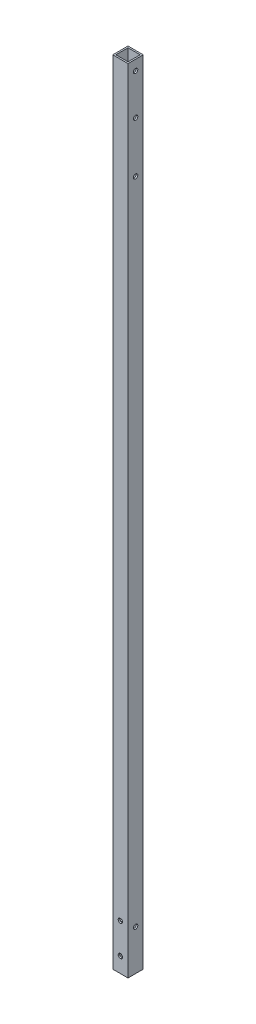
SolidWorks part; units mm, degrees
material "5052-H34"
ref_plane "正面" through (0, 0, 0) normal (0, 0, 1) x (1, 0, 0)
ref_plane "平面" through (0, 0, 0) normal (0, 1, 0) x (1, 0, 0)
ref_plane "右側面" through (0, 0, 0) normal (1, 0, 0) x (0, 0, -1)
sketch "ｽｹｯﾁ1" plane through (0, 0, 0) normal (0, 1, 0) x (1, 0, 0)
  line L1 (0, 0) -> (15, 0)
  line L2 (0, 0) -> (0, 15)
  line L3 (0, 15) -> (15, 15)
  line L4 (15, 0) -> (15, 15)
  dimension "D1" = 15
  dimension "D2" = 15
extrude "押し出し-薄板1" add sketch "ｽｹｯﾁ1" along normal blind 780 thin thin type one direction reverse wall 1.5
sketch "ｽｹｯﾁ2" plane through (15, 0, 0) normal (1, 0, 0) x (0, 0, -1)
  line L0 (7.5, 780) -> (7.5, 0) construction
  line L1 (0, 780) -> (15, 780) construction
  line L2 (0, 0) -> (15, 0) construction
  line L3 (15, 390) -> (0, 390) construction
  line L4 (15, 780) -> (15, 0) construction
  line L5 (0, 780) -> (0, 0) construction
  circle A4 centre (7.5, 730) radius 2.15
  circle A5 centre (7.5, 680) radius 2.15
  circle A6 centre (7.5, 40) radius 2.15
  circle A8 centre (7.5, 120) radius 2.15 construction
  circle A9 centre (7.5, 10) radius 2.15 construction
  circle A10 centre (7.5, 770) radius 2.15
  dimension "D2" = 50
  dimension "D3" = 7.5
  dimension "D4" = 80
  dimension "D5" = 640
  dimension "D7" = 4.3
  dimension "D8" = 30
  dimension "D9" = 7.5
  dimension "D10" = 10
  dimension "D6" = 4.3
  dimension "D11" = 10
extrude "ｶｯﾄ - 押し出し1" cut sketch "ｽｹｯﾁ2" against normal up to surface (15 mm away) up to face at (0, 390, -7.5)
sketch "ｽｹｯﾁ4" plane through (0, 0, 0) normal (0, 0, 1) x (1, 0, 0)
  line L0 (7.5, 780) -> (7.5, 0) construction
  line L1 (0, 780) -> (15, 780) construction
  line L2 (0, 0) -> (15, 0) construction
  circle A1 centre (7.5, 730) radius 2.05 construction
  circle A2 centre (7.5, 15) radius 2.15
  circle A3 centre (7.5, 45) radius 2.15
  dimension "D1" = 50
  dimension "D2" = 4.1
  dimension "D3" = 30
  dimension "D4" = 4.3
  dimension "D5" = 15
extrude "ｶｯﾄ - 押し出し2" cut sketch "ｽｹｯﾁ4" against normal up to surface (15 mm away) up to face at (7.5, 390, -15)
